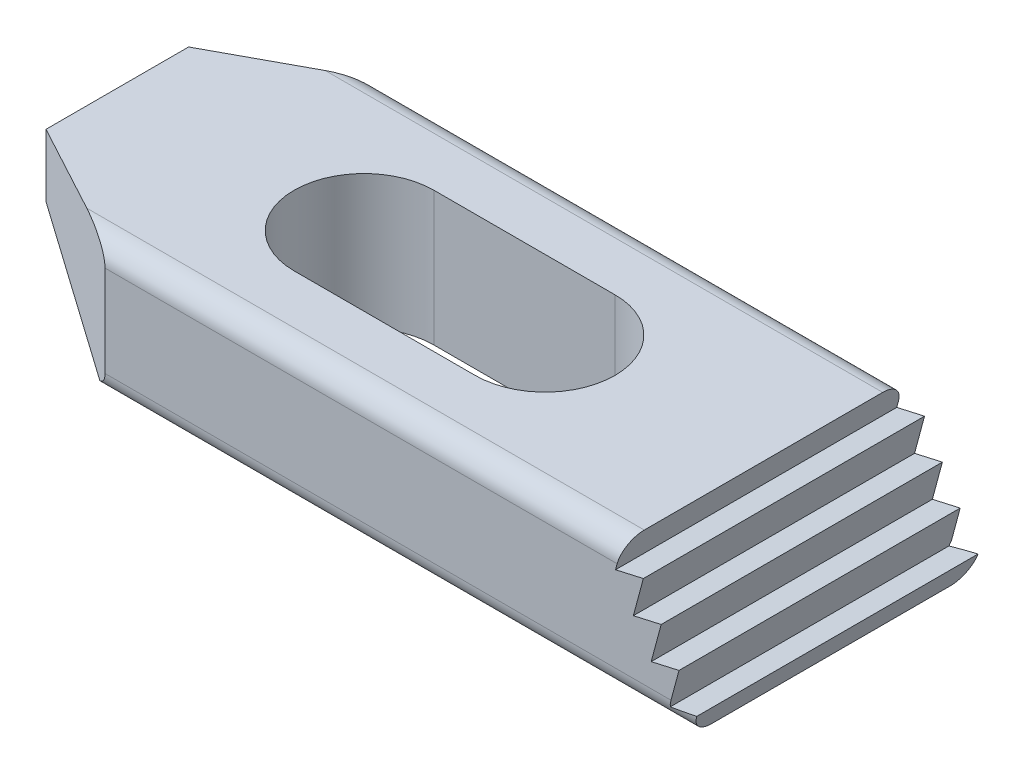
SolidWorks part; units mm, degrees
ref_plane "Front Plane" through (0, 0, 0) normal (0, 0, 1) x (1, 0, 0)
ref_plane "Top Plane" through (0, 0, 0) normal (0, 1, 0) x (1, 0, 0)
ref_plane "Right Plane" through (0, 0, 0) normal (1, 0, 0) x (0, 0, -1)
sketch "Sketch1" plane through (0, 0, 0) normal (0, 0, 1) x (1, 0, 0)
  line L1 (0, 0) -> (52.07, 0)
  line L2 (-11.4767, 11.938) -> (46.8118, 11.938)
  line L6 (46.8118, 11.938) -> (52.6583, 1.8115)
  line L7 (52.07, 0) -> (52.6583, 1.8115)
  line L8 (-11.4767, 11.938) -> (-11.4767, 6.35)
  line L9 (-11.4767, 6.35) -> (0, 0)
  dimension "D1" = 64.135
  dimension "D2" = 52.07
  dimension "D3" = 60
  dimension "D4" = 11.938
  dimension "D5" = 5.588
extrude "Boss-Extrude1" add sketch "Sketch1" along normal blind 25.0444
sketch "Sketch2" plane through (0, 0, 25.0444) normal (0, 0, 1) x (1, 0, 0)
  line L0 (51.0708, 4.5611) -> (50.1813, 1.2495)
  line L1 (50.1813, 1.2495) -> (52.6583, 1.8115)
  line L2 (52.6583, 1.8115) -> (46.8118, 11.938) construction
  line L3 (52.6583, 1.8115) -> (51.0708, 4.5611)
  dimension "D1" = 3.429
  dimension "D2" = 2.54
  dimension "D3" = 3.175
extrude "Cut-Extrude1" cut sketch "Sketch2" against normal through all
pattern_linear "LPattern1" count 11 spacing 3.175 along (-0.5, 0.866, 0) of "Cut-Extrude1"
sketch "Sketch3" plane through (0, 11.938, 0) normal (0, 1, 0) x (1, 0, 0)
  line L0 (10.4943, -12.5222) -> (26.6233, -12.5222) construction
  line L1 (10.4943, -6.2992) -> (26.6233, -6.2992)
  line L2 (10.4943, -18.7452) -> (26.6233, -18.7452)
  line L4 (-11.4767, -6.1722) -> (-0.0467, 0)
  line L5 (-11.4767, -25.0444) -> (-11.4767, 0) construction
  line L6 (46.0741, 0) -> (-11.4767, 0) construction
  line L7 (-11.4767, -12.5222) -> (46.0741, -12.5222) construction
  line L8 (46.0741, -25.0444) -> (46.0741, 0) construction
  line L9 (-11.4767, -6.1722) -> (-11.4767, 0)
  line L10 (-11.4767, 0) -> (-0.0467, 0)
  line L11 (-11.4767, -25.0444) -> (-0.0467, -25.0444)
  line L12 (-11.4767, -18.8722) -> (-11.4767, -25.0444)
  line L13 (-11.4767, -18.8722) -> (-0.0467, -25.0444)
  arc A0 (10.4943, -6.2992) -> (10.4943, -18.7452) centre (10.4943, -12.5222) ccw
  arc A1 (26.6233, -18.7452) -> (26.6233, -6.2992) centre (26.6233, -12.5222) ccw
  point P2 (18.5588, -12.5222)
  point P22 (32.8463, -12.5222)
  point P24 (4.2713, -12.5222)
  dimension "D1" = 6.35
  dimension "D2" = 11.43
  dimension "D3" = 28.575
  dimension "D4" = 12.446
  dimension "D5" = 15.748
extrude "Cut-Extrude2" cut sketch "Sketch3" against normal through all
fillet "Fillet1" radius 1.905 4 edges at (23.0137, 11.938, 25.0444) (23.0137, 11.938, 0) (26.035, 0, 0) (26.035, 0, 25.0444)
